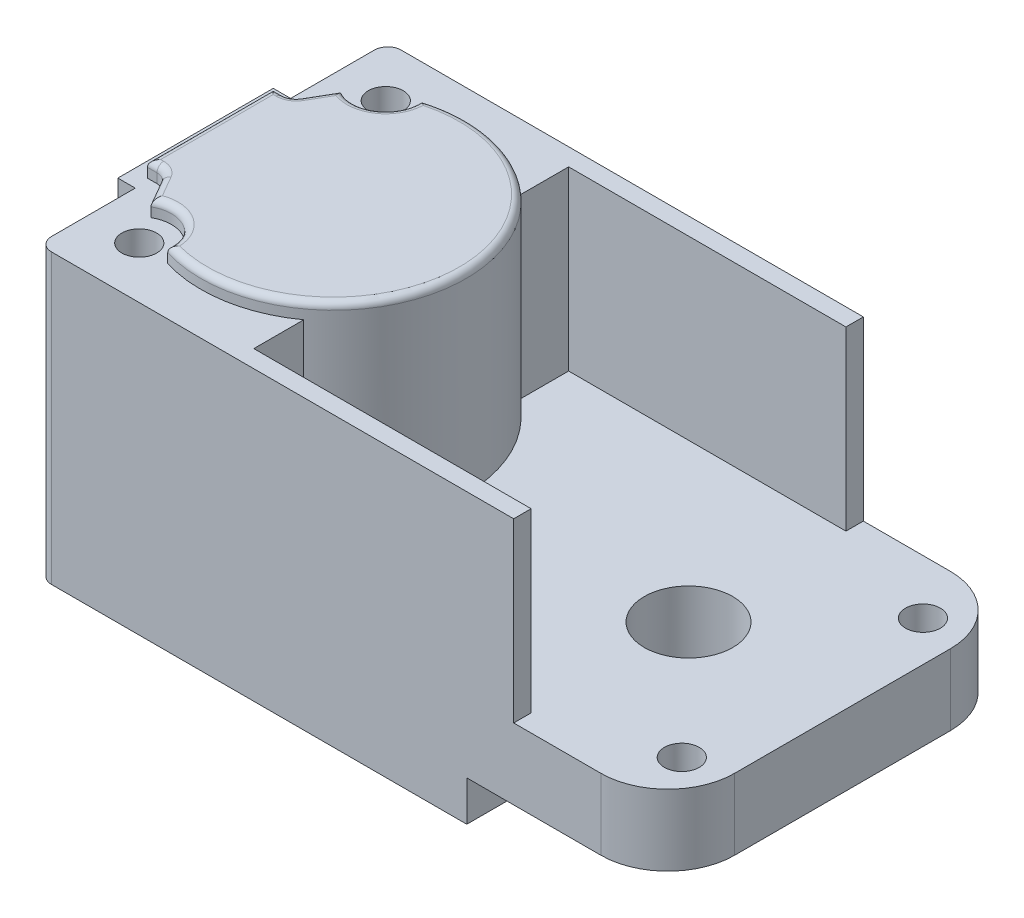
SolidWorks part; units mm, degrees
ref_plane "Front" through (0, 0, 0) normal (0, 0, 1) x (1, 0, 0)
ref_plane "Top" through (0, 0, 0) normal (0, 1, 0) x (1, 0, 0)
ref_plane "Right" through (0, 0, 0) normal (1, 0, 0) x (0, 0, -1)
sketch "Sketch1" plane through (0, 0, 0) normal (0, 1, 0) x (1, 0, 0)
  line L0 (11.5, 0) -> (-36.8, 0) construction
  line L1 (-34.5, 13.05) -> (6.5, 13.05)
  line L2 (-35.5, 12.05) -> (-35.5, 5.8)
  line L3 (-34.5, -13.05) -> (6.5, -13.05)
  line L4 (11.5, 8.05) -> (11.5, -8.05)
  line L5 (-35.5, -5.8) -> (-35.5, -12.05)
  line L6 (-35.5, 5.8) -> (-36.8, 5.8)
  line L8 (-35.5, -5.8) -> (-36.8, -5.8)
  line L9 (-36.8, 5.8) -> (-36.8, -5.8)
  arc A0 (11.5, 8.05) -> (6.5, 13.05) centre (6.5, 8.05) ccw
  arc A1 (11.5, -8.05) -> (6.5, -13.05) centre (6.5, -8.05) cw
  circle A2 centre (-31.8, 9.2) radius 1.3
  circle A3 centre (8.5, 9) radius 1.3
  arc A4 (-35.5, 12.05) -> (-34.5, 13.05) centre (-34.5, 12.05) cw
  arc A5 (-34.5, -13.05) -> (-35.5, -12.05) centre (-34.5, -12.05) cw
  circle A6 centre (8.5, -9) radius 1.3
  circle A7 centre (-31.8, -9.2) radius 1.3
  point P9 (11.5, 13.05)
  point P22 (-35.5, 13.05)
  dimension "D4" = 5
  dimension "D7" = 2.6
  dimension "D8" = 2.6
  dimension "D11" = 1
  dimension "D1" = 11.5
  dimension "D2" = 47
  dimension "D3" = 26.1
  dimension "D5" = 11.6
  dimension "D6" = 1.3
  dimension "D9" = 9.2
  dimension "D10" = 3.7
  dimension "D12" = 9
  dimension "D13" = 3
extrude "Extrude1" add sketch "Sketch1" along normal blind 21.5
sketch "Sketch2" plane through (0, 21.5, 0) normal (0, 1, 0) x (-1, 0, 0)
  line L0 (36.8, 0) -> (15.2745, 0) construction
  line L1 (36.8, -5.8) -> (36.8, 5.8) construction
  line L2 (35.5, -12.05) -> (35.5, -5.8) construction
  line L7 (33.0007, -7.1219) -> (34.1113, -5.1997)
  line L8 (33.0007, 7.1219) -> (34.1113, 5.1997)
  line L9 (34.9771, 4.7) -> (35.7, 4.7)
  line L10 (35.7, 4.7) -> (35.5, 4.7)
  line L11 (35.7, -4.7) -> (35.7, 4.7)
  line L12 (35.5, -4.7) -> (35.7, -4.7)
  line L14 (35.7, -4.7) -> (35.7, 4.7)
  line L15 (34.9771, -4.7) -> (35.7, -4.7)
  arc A0 (29.4143, 9.4613) -> (29.4143, -9.4613) centre (26.5, 0) ccw
  arc A2 (34.1113, -5.1997) -> (34.9771, -4.7) centre (34.9771, -5.7) cw
  circle A3 centre (31.8, -9.2) radius 2.4
  arc A4 (33.0007, -7.1219) -> (29.4143, -9.4613) centre (31.8, -9.2) ccw
  arc A5 (33.0007, 7.1219) -> (29.4143, 9.4613) centre (31.8, 9.2) cw
  arc A6 (34.1113, 5.1997) -> (34.9771, 4.7) centre (34.9771, 5.7) ccw
  point P22 (34.4, -4.7)
  point P28 (35.7, 0)
  dimension "D2" = 19.8
  dimension "D6" = 1
  dimension "D1" = 9
  dimension "D5" = 1.3
  dimension "D3" = 1.1
  dimension "D4" = 1.1
extrude "Extrude2" add sketch "Sketch2" along normal blind 1.2
fillet "Fillet1" radius 0.5 10 edges at (-33.556, 22.7, 6.1608) (-34.4773, 22.7, 4.8339) (-35.3386, 22.7, 4.7) (-35.7, 22.7, 0) (-35.3386, 22.7, -4.7) (-34.4773, 22.7, -4.8339) (-33.556, 22.7, -6.1608) (-30.4888, 22.7, -7.1899) (-16.6, 22.7, 0) (-30.4888, 22.7, 7.1899)
sketch "Sketch3" plane through (0, 21.5, 0) normal (0, 1, 0) x (-1, 0, 0)
  line L0 (20.7, 8.0231) -> (20.7, 11.75)
  line L8 (20.7, -11.75) -> (20.7, -8.0231)
  line L9 (35.5, -12.05) -> (35.5, -5.8) construction
  line L16 (-6.5, -11.75) -> (34.2, -11.75)
  line L17 (34.2, -11.75) -> (34.2, -4.5)
  line L18 (34.2, -4.5) -> (35.5, -4.5)
  line L19 (35.5, -4.5) -> (35.5, 4.5)
  line L20 (35.5, 4.5) -> (34.2, 4.5)
  line L21 (34.2, 4.5) -> (34.2, 11.75)
  line L22 (34.2, 11.75) -> (-6.5, 11.75)
  line L23 (-10.2, 8.05) -> (-10.2, -8.05)
  line L24 (-6.5, -11.75) -> (20.7, -11.75)
  line L30 (20.7, 11.75) -> (-6.5, 11.75)
  line L31 (-10.2, 7.4508) -> (-10.2, -7.4508)
  circle A6 centre (-8.5, -9) radius 2.3
  arc A7 (-8.2866, -11.2901) -> (-10.2, -7.4508) centre (-8.5, -9) ccw
  arc A8 (-10.2, -8.05) -> (-6.5, -11.75) centre (-6.5, -8.05) ccw
  arc A9 (-6.5, 11.75) -> (-10.2, 8.05) centre (-6.5, 8.05) ccw
  arc A10 (-8.2866, -11.2901) -> (-6.5, -11.75) centre (-6.5, -8.05) ccw
  arc A11 (-6.5, 11.75) -> (-8.2866, 11.2901) centre (-6.5, 8.05) ccw
  arc A12 (29.4143, 9.4613) -> (29.4143, -9.4613) centre (26.5, 0) ccw construction
  arc A13 (20.7, 8.0231) -> (20.7, -8.0231) centre (26.5, 0) ccw
  circle A17 centre (-8.5, 9) radius 2.3
  arc A18 (-10.2, 7.4508) -> (-8.2866, 11.2901) centre (-8.5, 9) ccw
  dimension "D4" = 1
  dimension "D3" = 14.8
  dimension "D1" = 1.3
  dimension "D2" = 1
sketch "Sketch4" plane through (0, 21.5, 0) normal (0, 1, 0) x (-1, 0, 0)
  line L0 (-6.5, -13.05) -> (34.5, -13.05) construction
  line L1 (0, -13.05) -> (-11.5, -13.05)
  line L2 (0, -13.05) -> (0, 13.05)
  line L3 (0, 13.05) -> (-11.5, 13.05)
  line L4 (-11.5, -13.05) -> (-11.5, 13.05)
  line L5 (-11.5, 8.05) -> (-11.5, -8.05) construction
  line L6 (34.5, 13.05) -> (-6.5, 13.05) construction
extrude "Cut-Extrude2" cut sketch "Sketch4" against normal blind 13.2
sketch "Sketch5" plane through (0, 0, 0) normal (0, -1, 0) x (1, 0, 0)
  line L0 (-3.5, -13.05) -> (-3.5, 13.05)
  line L8 (11.5, -8.05) -> (11.5, 8.05)
  line L9 (6.5, 13.05) -> (-34.5, 13.05)
  line L10 (-35.5, 12.05) -> (-35.5, 5.8)
  line L11 (-35.5, 5.8) -> (-36.8, 5.8)
  line L12 (-36.8, 5.8) -> (-36.8, -5.8)
  line L13 (-36.8, -5.8) -> (-35.5, -5.8)
  line L14 (-35.5, -5.8) -> (-35.5, -12.05)
  line L15 (-34.5, -13.05) -> (6.5, -13.05)
  line L16 (11.5, -8.05) -> (11.5, 8.05)
  line L17 (6.5, 13.05) -> (-3.5, 13.05)
  line L23 (-3.5, -13.05) -> (6.5, -13.05)
  arc A4 (6.5, -13.05) -> (11.5, -8.05) centre (6.5, -8.05) ccw
  arc A5 (11.5, 8.05) -> (6.5, 13.05) centre (6.5, 8.05) ccw
  arc A6 (-34.5, 13.05) -> (-35.5, 12.05) centre (-34.5, 12.05) ccw
  arc A7 (-35.5, -12.05) -> (-34.5, -13.05) centre (-34.5, -12.05) ccw
  arc A8 (6.5, -13.05) -> (11.5, -8.05) centre (6.5, -8.05) ccw
  arc A9 (11.5, 8.05) -> (6.5, 13.05) centre (6.5, 8.05) ccw
  dimension "D2" = 15
  dimension "D1" = 0
extrude "Cut-Extrude3" cut sketch "Sketch5" against normal blind 3
extrude "Cut-Extrude4" cut sketch "Sketch3" against normal blind 13.2
sketch "Sketch6" plane through (0, 0, 0) normal (0, -1, 0) x (1, 0, 0)
  line L0 (-3.5, 0) -> (14.7135, 0) construction
  line L1 (-3.5, 13.05) -> (-3.5, -13.05) construction
  line L2 (11.5, -8.05) -> (11.5, 8.05) construction
  circle A0 centre (0, 0) radius 3.3
  dimension "D1" = 6.6
  dimension "D2" = 11.5
extrude "Cut-Extrude5" cut sketch "Sketch6" against normal through all
ref_plane "Plane1" through (0, 8.8, 0) normal (0, 1, 0) x (-1, 0, 0)
